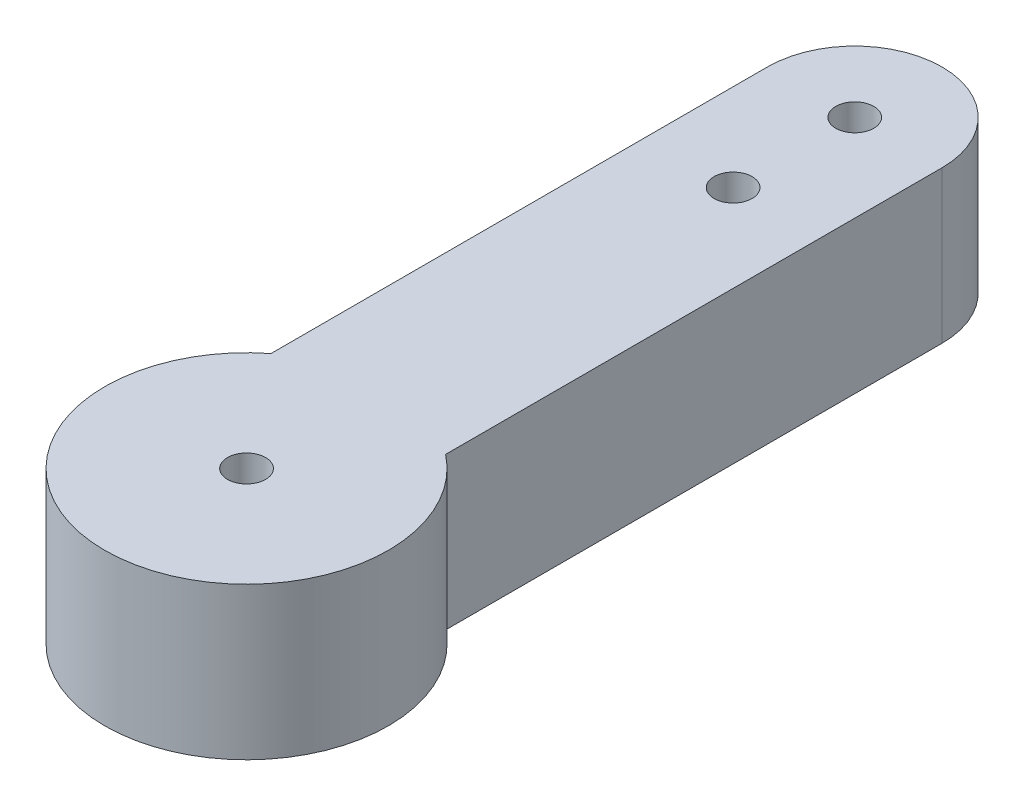
SolidWorks part; units mm, degrees
ref_plane "Front Plane" through (0, 0, 0) normal (0, 0, 1) x (1, 0, 0)
ref_plane "Top Plane" through (0, 0, 0) normal (0, 1, 0) x (1, 0, 0)
ref_plane "Right Plane" through (0, 0, 0) normal (1, 0, 0) x (0, 0, -1)
sketch "Sketch1" plane through (0, 0, 0) normal (0, 1, 0) x (1, 0, 0)
  line L2 (-3.6467, 25.4) -> (-3.6467, 4.6666)
  line L4 (3.6467, 25.4) -> (3.6467, 4.6666)
  circle A0 centre (0, 0) radius 5.9225
  circle A1 centre (0, 0) radius 4.1947
  arc A2 (3.6467, 25.4) -> (-3.6467, 25.4) centre (0, 25.4) ccw
  circle A3 centre (0, 25.4) radius 0.7937
  circle A4 centre (0, 20.32) radius 0.7937
  circle A5 centre (0, 0) radius 0.7937
  dimension "D2" = 1.5875
  dimension "D1" = 25.4
  dimension "D3" = 5.08
extrude "Boss-Extrude1" add sketch "Sketch1" along normal blind 6.35 contours A0 A1 | A1 A5 | L4 A2 L2 A0 A4 A3
